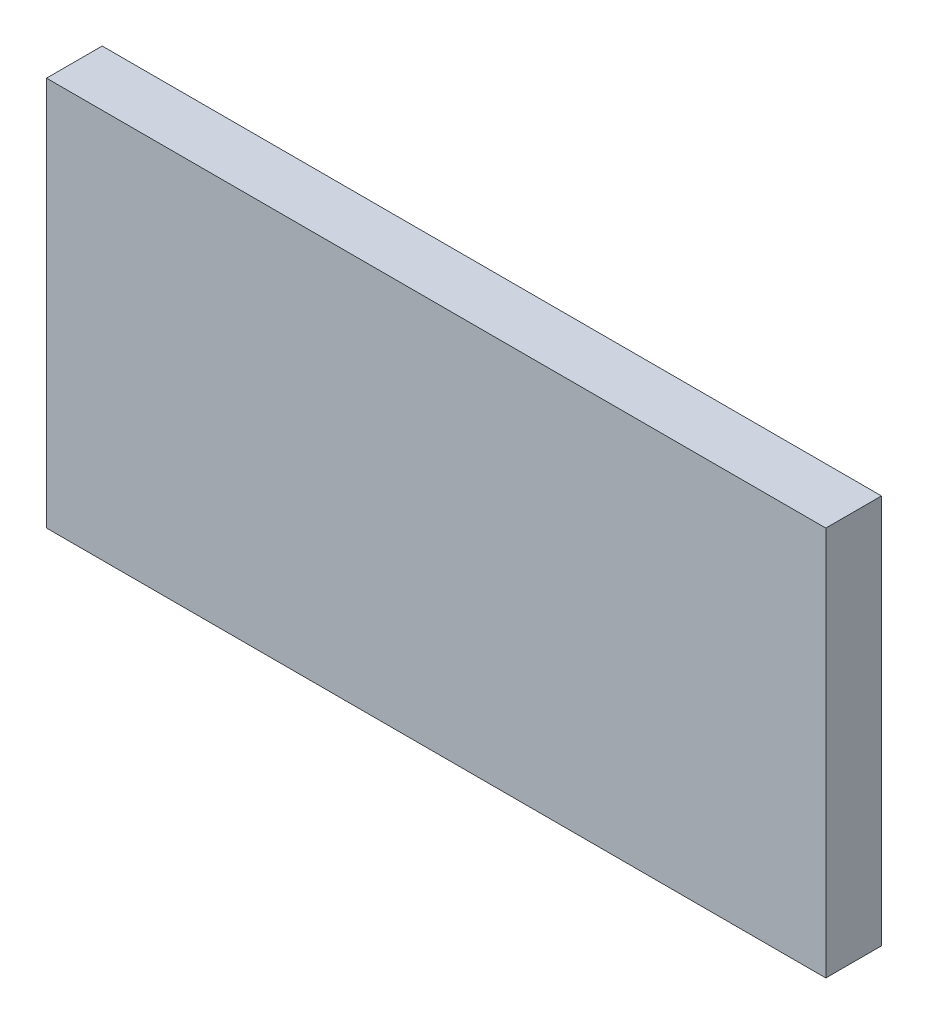
SolidWorks part; units mm, degrees
material "Acrylic (Medium-high impact)"
ref_plane "Front Plane" through (0, 0, 0) normal (0, 0, 1) x (1, 0, 0)
ref_plane "Top Plane" through (0, 0, 0) normal (0, 1, 0) x (1, 0, 0)
ref_plane "Right Plane" through (0, 0, 0) normal (1, 0, 0) x (0, 0, -1)
sketch "Sketch1" plane through (0, 0, 0) normal (0, 0, 1) x (1, 0, 0)
  line L1 (0, 0) -> (-88.9, 0)
  line L2 (0, 0) -> (0, 44.45)
  line L3 (0, 44.45) -> (-88.9, 44.45)
  line L4 (-88.9, 0) -> (-88.9, 44.45)
  dimension "D1" = 88.9
  dimension "D2" = 44.45
extrude "Boss-Extrude1" add sketch "Sketch1" along normal blind 6.35
